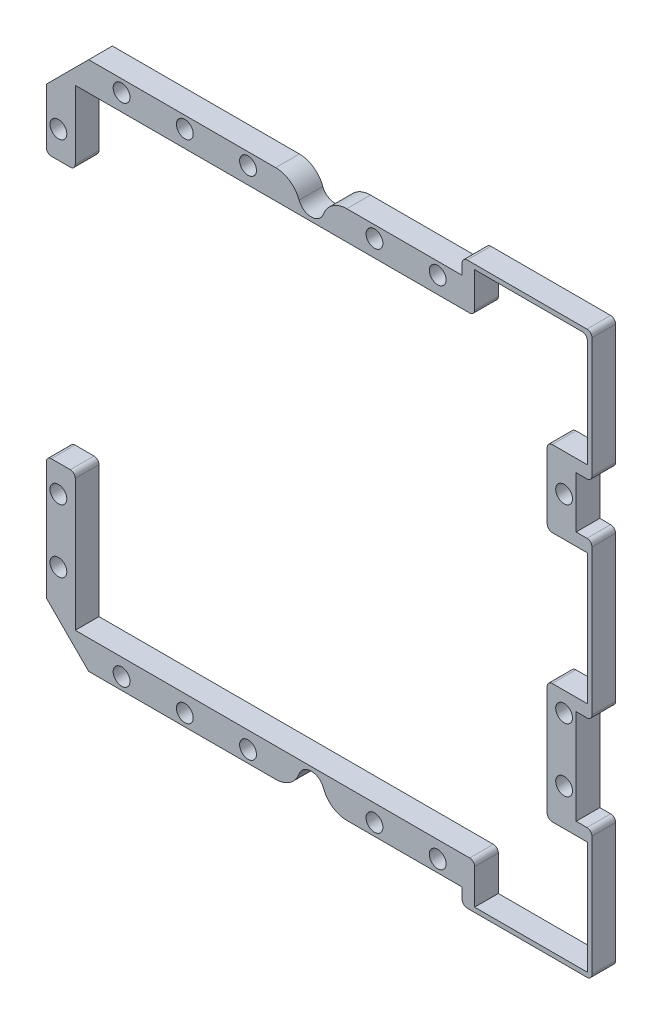
SolidWorks part; units mm, degrees
ref_plane "Front Plane" through (0, 0, 0) normal (0, 0, 1) x (1, 0, 0)
ref_plane "Top Plane" through (0, 0, 0) normal (0, 1, 0) x (1, 0, 0)
ref_plane "Right Plane" through (0, 0, 0) normal (1, 0, 0) x (0, 0, -1)
sketch "Sketch1" plane through (0, 0, 0) normal (0, 0, 1) x (1, 0, 0)
  line L0 (106.426, 0) -> (106.426, -212.852) construction
  line L1 (11.6134, -11.6134) -> (201.2386, -11.6134)
  line L2 (11.6134, -11.6134) -> (11.6134, -201.2386)
  line L3 (11.6134, -201.2386) -> (201.2386, -201.2386)
  line L4 (201.2386, -11.6134) -> (201.2386, -201.2386)
  line L5 (0, -106.426) -> (212.852, -106.426) construction
  line L6 (0, -16.9978) -> (16.9978, 0)
  line L7 (0, 0) -> (212.852, 0)
  line L8 (0, 0) -> (0, -212.852)
  line L9 (0, -212.852) -> (212.852, -212.852)
  line L10 (212.852, 0) -> (212.852, -212.852)
  line L11 (195.8542, 0) -> (212.852, -16.9978)
  line L12 (212.852, -195.8542) -> (195.8542, -212.852)
  line L13 (16.9978, -212.852) -> (0, -195.8542)
  line L14 (0, -41.101) -> (11.6134, -41.101)
  line L15 (0, -146.351) -> (11.6134, -146.351)
  line L16 (172.0761, 0) -> (172.0761, -11.6134)
  line L17 (201.2386, -40.7759) -> (212.852, -40.7759)
  line L18 (201.2386, -71.426) -> (212.852, -71.426)
  line L19 (201.2386, -123.926) -> (212.852, -123.926)
  line L20 (201.2386, -172.0761) -> (212.852, -172.0761)
  line L21 (172.0761, -201.2386) -> (172.0761, -212.852)
  line L22 (7.366, -46.101) -> (-4.064, -46.101) construction
  line L23 (7.366, -141.351) -> (-10.8774, -141.351) construction
  line L24 (177.0761, -4.826) -> (172.0761, -4.826) construction
  line L25 (172.0761, 4.5) -> (172.0761, 0)
  line L26 (217.352, -40.7759) -> (217.352, 4.5)
  line L27 (217.352, 4.5) -> (172.0761, 4.5)
  line L29 (167.0761, 0) -> (167.0761, 6.35)
  line L30 (167.0761, 6.35) -> (219.202, 6.35)
  line L31 (219.202, 6.35) -> (219.202, -45.7759)
  line L32 (219.202, -45.7759) -> (212.852, -45.7759)
  line L33 (167.0761, 0) -> (0, 0)
  line L34 (212.852, -71.426) -> (217.352, -71.426)
  line L35 (217.352, -71.426) -> (217.352, -123.926)
  line L36 (217.352, -123.926) -> (212.852, -123.926)
  line L37 (212.852, -128.926) -> (219.202, -128.926)
  line L38 (219.202, -128.926) -> (219.202, -66.426)
  line L39 (219.202, -66.426) -> (212.852, -66.426)
  line L40 (172.0761, -212.852) -> (172.0761, -217.352)
  line L41 (172.0761, -217.352) -> (217.352, -217.352)
  line L42 (217.352, -217.352) -> (217.352, -172.0761)
  line L43 (217.352, -172.0761) -> (212.852, -172.0761)
  line L44 (167.0761, -212.852) -> (167.0761, -219.202)
  line L45 (167.0761, -219.202) -> (219.202, -219.202)
  line L46 (219.202, -219.202) -> (219.202, -167.0761)
  line L47 (219.202, -167.0761) -> (212.852, -167.0761)
  line L49 (212.852, -40.7759) -> (217.352, -40.7759)
  circle A1 centre (30.226, -4.826) radius 3.38
  circle A2 centre (55.626, -4.826) radius 3.38
  circle A3 centre (81.026, -4.826) radius 3.38
  circle A5 centre (131.826, -4.826) radius 3.38
  circle A6 centre (157.226, -4.826) radius 3.38
  circle A7 centre (182.626, -4.826) radius 3.38
  circle A8 centre (208.026, -30.226) radius 3.38
  circle A9 centre (208.026, -55.626) radius 3.38
  circle A10 centre (208.026, -81.026) radius 3.38
  circle A11 centre (208.026, -106.426) radius 5.1943
  circle A12 centre (208.026, -182.626) radius 3.38
  circle A13 centre (208.026, -157.226) radius 3.38
  circle A14 centre (208.026, -131.826) radius 3.38
  circle A15 centre (182.626, -208.026) radius 3.38
  circle A16 centre (157.226, -208.026) radius 3.38
  circle A17 centre (131.826, -208.026) radius 3.38
  circle A18 centre (106.426, -208.026) radius 5.1943
  circle A19 centre (30.226, -208.026) radius 3.38
  circle A20 centre (55.626, -208.026) radius 3.38
  circle A21 centre (81.026, -208.026) radius 3.38
  circle A22 centre (4.826, -182.626) radius 3.38
  circle A23 centre (4.826, -157.226) radius 3.38
  circle A24 centre (4.826, -131.826) radius 3.38
  circle A25 centre (4.826, -106.426) radius 5.1943
  circle A26 centre (4.826, -30.226) radius 3.38
  circle A27 centre (4.826, -55.626) radius 3.38
  circle A28 centre (4.826, -81.026) radius 3.38
  circle A29 centre (106.426, -4.826) radius 3.38 [skipped]
  circle A30 centre (106.426, -4.826) radius 5.1943
  circle A31 centre (182.626, -4.826) radius 5.5499 construction
  point P5 (106.426, 0)
  point P6 (106.426, -11.6134)
  point P7 (0, -106.426)
  point P12 (11.6134, -106.426)
  point P33 (106.426, -106.426)
  point P85 (106.426, -106.426)
  point P134 (217.852, -217.852)
  point P135 (222.852, -139.4143)
  dimension "D4" = 6.76
  dimension "D12" = 10.3886
  dimension "D3" = 45
  dimension "D1" = 212.852
  dimension "D2" = 189.6252
  dimension "D7" = 12.0193
  dimension "D8" = 30.226
  dimension "D9" = 4.826
  dimension "D6" = 25.4
  dimension "D11" = 25.4
  dimension "D13" = 5
  dimension "D14" = 5
  dimension "D15" = 5
  dimension "D16" = 40.7759
  dimension "D17" = 40.7759
  dimension "D18" = 4.5
  dimension "D19" = 6.35
  dimension "D20" = 5
  dimension "D21" = 35
  dimension "D22" = 17.5
  dimension "D23" = 40.7759
  dimension "D24" = 5
  dimension "D25" = 5
  dimension "D26" = 5
  dimension "D27" = 5
  dimension "D5" = 7
  dimension "D10" = 4
extrude "Boss-Extrude1" add sketch "Sketch1" along normal blind 9.525 contours L38 L39 L10 L34 L35 L36 L37 | L4 L18 L10 L17 A9 | L4 L20 L10 L19 A14 A13 | L46 L47 L10 L43 L42 L41 L40 L9 L44 L45 | L49 L10 L32 L31 L30 L29 L7 L25 L27 L26 | A30 L7 L6 L8 L14 L2 L1 L16 A26 A6 A5 A3 A2 A1 | A18 L9 L21 L3 L2 L15 L8 L13 A23 A22 A21 A20 A19 A17 A16
fillet "Fillet1" radius 10 3 edges at (108.3471, -212.852, 4.7625) (104.5049, -212.852, 4.7625) (108.3471, 0, 4.7625)
fillet "Fillet2" radius 2 19 edges at (0, -146.351, 4.7625) (11.6134, -146.351, 4.7625) (11.6134, -41.101, 4.7625) (0, -41.101, 4.7625) (172.0761, -11.6134, 4.7625) (167.0761, 6.35, 4.7625) (172.0761, -201.2386, 4.7625) (167.0761, -219.202, 4.7625) (219.202, -219.202, 4.7625) (219.202, -167.0761, 4.7625) (201.2386, -172.0761, 4.7625) (219.202, -128.926, 4.7625) (201.2386, -123.926, 4.7625) (201.2386, -71.426, 4.7625) (219.202, -66.426, 4.7625) (201.2386, -40.7759, 4.7625) (219.202, -45.7759, 4.7625) (219.202, 6.35, 4.7625) (217.352, 4.5, 4.7625)
equation "\"D14@Sketch1\"=\"D13@Sketch1\""
equation "\"D25@Sketch1\"=\"D24@Sketch1\""
equation "\"D24@Sketch1\"=\"D20@Sketch1\""
equation "\"D26@Sketch1\"=\"D20@Sketch1\""
equation "\"D27@Sketch1\"=\"D26@Sketch1\""
